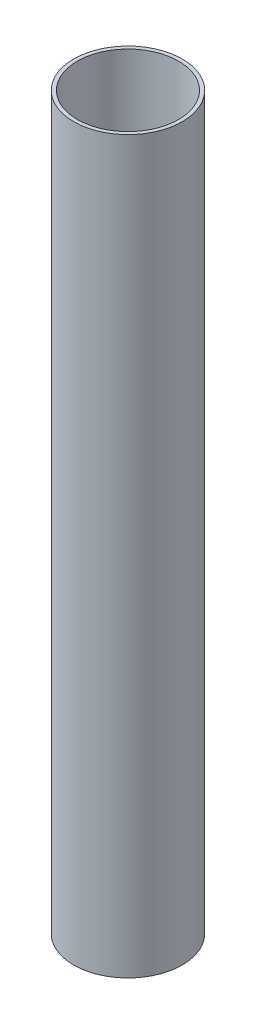
SolidWorks part; units mm, degrees
material "S-Glass Fiber"
ref_plane "Front Plane" through (0, 0, 0) normal (0, 0, 1) x (1, 0, 0)
ref_plane "Top Plane" through (0, 0, 0) normal (0, 1, 0) x (1, 0, 0)
ref_plane "Right Plane" through (0, 0, 0) normal (1, 0, 0) x (0, 0, -1)
sketch "Sketch1" plane through (0, 0, 0) normal (0, 1, 0) x (1, 0, 0)
  circle A0 centre (0, 0) radius 19.3675
  circle A1 centre (0, 0) radius 20.7645
  dimension "D1" = 38.735
  dimension "D2" = 41.529
extrude "Boss-Extrude1" add sketch "Sketch1" along normal blind 279.4
